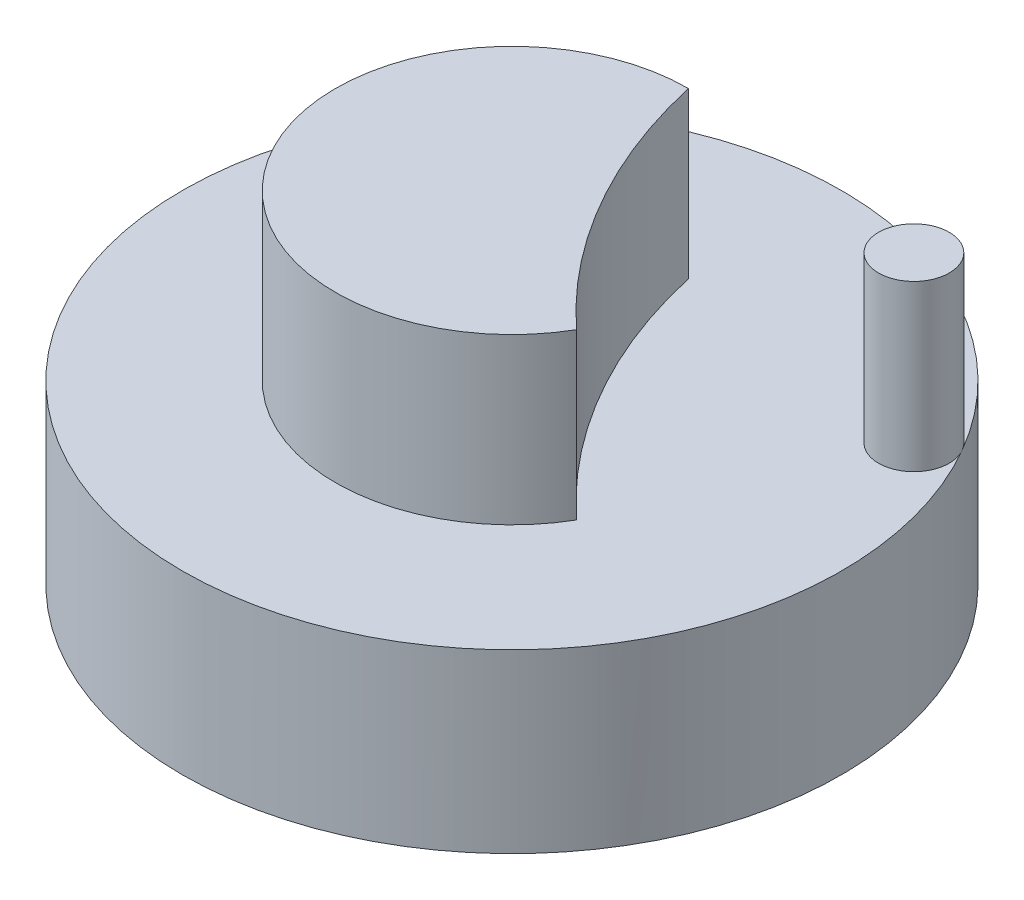
SolidWorks part; units mm, degrees
ref_plane "Front Plane" through (0, 0, 0) normal (0, 0, 1) x (1, 0, 0)
ref_plane "Top Plane" through (0, 0, 0) normal (0, 1, 0) x (1, 0, 0)
ref_plane "Right Plane" through (0, 0, 0) normal (1, 0, 0) x (0, 0, -1)
sketch "Sketch1" plane through (0, 0, 0) normal (0, 1, 0) x (1, 0, 0)
  line L2 (25.9808, -115) -> (48.4267, -78.1194) construction
  line L3 (0, -70) -> (43.1625, -69.0016) construction
  line L4 (25.9808, -115) -> (48.4267, -78.1194)
  line L5 (0, -70) -> (43.1625, -69.0016)
  arc A0 (0, -70) -> (25.9808, -115) centre (84.7241, -51.0845) ccw construction
  circle A1 centre (43.3013, -75) radius 6 construction
  circle A2 centre (0, -100) radius 30 construction
  arc A3 (0, -70) -> (25.9808, -115) centre (84.7241, -51.0845) ccw
  circle A4 centre (43.3013, -75) radius 6
  arc A5 (0, -70) -> (25.9808, -115) centre (0, -100) ccw
extrude "Boss-Extrude1" add sketch "Sketch1" along normal blind 28 contours A3 A5 | A4 L4
sketch "Sketch2" plane through (0, 0, 0) normal (0, 1, 0) x (1, 0, 0)
  circle A0 centre (0, -100) radius 56 construction
  circle A1 centre (0, -100) radius 56
extrude "Boss-Extrude3" add sketch "Sketch2" against normal blind 30
sketch "Sketch3" plane through (0, -30, 0) normal (0, -1, 0) x (1, 0, 0)
  circle A0 centre (0, 100) radius 15
  dimension "D1" = 30
extrude "Cut-Extrude1" cut sketch "Sketch3" against normal blind 29
